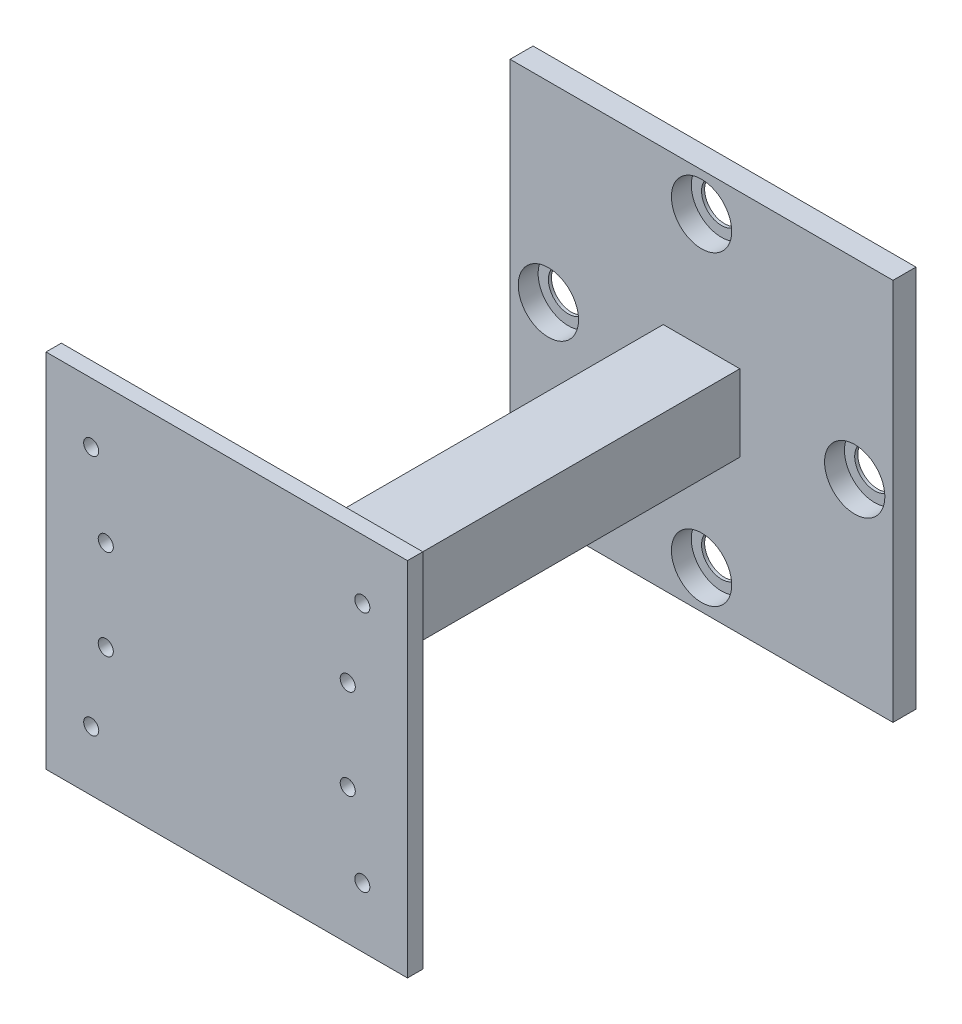
SolidWorks part; units mm, degrees
ref_plane "Front Plane" through (0, 0, 0) normal (0, 0, 1) x (1, 0, 0)
ref_plane "Top Plane" through (0, 0, 0) normal (0, 1, 0) x (1, 0, 0)
ref_plane "Right Plane" through (0, 0, 0) normal (1, 0, 0) x (0, 0, -1)
sketch "Sketch2" plane through (0, 0, 0) normal (0, 0, 1) x (1, 0, 0)
  line L0 (0, 0) -> (63.5, 0)
  line L1 (63.5, 0) -> (63.5, 63.5)
  line L2 (63.5, 63.5) -> (0, 63.5)
  line L3 (0, 63.5) -> (0, 0)
  dimension "D1" = 63.5
  dimension "D2" = 63.5
extrude "Boss-Extrude2" add sketch "Sketch2" along normal blind 3.81
sketch "Sketch3" plane through (0, 0, 3.81) normal (0, 0, 1) x (1, 0, 0)
  line L0 (25.4, 38.1) -> (25.4, 25.4)
  line L1 (25.4, 25.4) -> (38.1, 25.4)
  line L2 (38.1, 25.4) -> (38.1, 38.1)
  line L3 (38.1, 38.1) -> (25.4, 38.1)
  line L4 (0, 0) -> (63.5, 0) construction
  line L5 (63.5, 0) -> (63.5, 63.5) construction
  dimension "D1" = 12.7
  dimension "D2" = 12.7
  dimension "D3" = 25.4
  dimension "D4" = 25.4
extrude "Boss-Extrude3" add sketch "Sketch3" along normal blind 76.2
sketch "Sketch14" plane through (0, 0, 80.01) normal (0, 0, 1) x (1, 0, 0)
  line L0 (1.778, 61.722) -> (61.722, 61.722)
  line L1 (61.722, 61.722) -> (61.722, 1.778)
  line L2 (61.722, 1.778) -> (1.778, 1.778)
  line L3 (1.778, 1.778) -> (1.778, 61.722)
  line L4 (63.5, 63.5) -> (0, 63.5) construction
  line L5 (0, 63.5) -> (0, 0) construction
  dimension "D1" = 59.944
  dimension "D2" = 59.944
  dimension "D3" = 1.778
  dimension "D4" = 1.778
extrude "Boss-Extrude6" add sketch "Sketch14" along normal blind 2.54
hole_wizard "CBORE for M6 SBHCS2" positions "Sketch17" profile "Sketch16" counterbore size "M6" standard "ANSI Metric"
sketch "Sketch17" plane through (0, 0, 3.81) normal (0, 0, 1) x (1, 0, 0)
  line L0 (63.5, 63.5) -> (0, 63.5) construction
  line L1 (0, 63.5) -> (0, 0) construction
  line L2 (0, 0) -> (63.5, 0) construction
  line L3 (63.5, 0) -> (63.5, 63.5) construction
  point P0 (57.15, 31.75)
  point P2 (31.75, 6.35)
  point P4 (31.75, 57.15)
  point P6 (6.35, 31.75)
  dimension "D1" = 6.35
  dimension "D2" = 31.75
  dimension "D3" = 6.35
  dimension "D4" = 31.75
  dimension "D5" = 6.35
  dimension "D6" = 31.75
  dimension "D7" = 6.35
  dimension "D8" = 31.75
sketch "Sketch16" plane through (57.15, 31.75, 3.81) normal (1, 0, 0) x (0, -1, 0)
  line L0 (0, 0) -> (0, 9.6028)
  line L1 (0, 9.6028) -> (3.3, 7.62)
  line L2 (3.3, 7.62) -> (3.3, 3.3)
  line L3 (3.3, 3.3) -> (5, 3.3)
  line L4 (5, 3.3) -> (5, 0)
  line L5 (5, 0) -> (0, 0)
  line L10 (0, 9.6028) -> (-3.3, 7.62) construction
  line L11 (0, -6.35) -> (0, 107.95) construction
  dimension "Hole Dia." = 6.6
  dimension "Hole Depth" = 7.62
  dimension "C'Bore Dia." = 10
  dimension "C'Bore Depth" = 3.3
  dimension "Drill Angle" = 118
hole_wizard "Tap Drill for M3x0.5 Tap2" positions "Sketch18" profile "Sketch19" hole size "M3x0.5" standard "ANSI Metric"
sketch "Sketch18" plane through (0, 0, 82.55) normal (0, 0, 1) x (1, 0, 0)
  line L0 (61.722, 1.778) -> (61.722, 61.722) construction
  line L1 (1.778, 1.778) -> (61.722, 1.778) construction
  line L2 (1.778, 61.722) -> (1.778, 1.778) construction
  line L3 (61.722, 61.722) -> (1.778, 61.722) construction
  point P0 (9.271, 51.816)
  point P2 (9.271, 11.684)
  point P4 (54.229, 11.684)
  point P6 (54.229, 51.816)
  point P8 (11.684, 39.243)
  point P10 (11.684, 24.257)
  point P12 (51.816, 39.243)
  point P14 (51.816, 24.257)
  dimension "D1" = 7.493
  dimension "D2" = 9.906
  dimension "D3" = 7.493
  dimension "D4" = 9.906
  dimension "D5" = 7.493
  dimension "D6" = 9.906
  dimension "D7" = 7.493
  dimension "D8" = 9.906
  dimension "D9" = 9.906
  dimension "D10" = 22.479
  dimension "D11" = 9.906
  dimension "D12" = 22.479
  dimension "D13" = 9.906
  dimension "D14" = 22.479
  dimension "D15" = 9.906
  dimension "D16" = 22.479
sketch "Sketch19" plane through (9.271, 51.816, 82.55) normal (1, 0, 0) x (0, -1, 0)
  line L0 (0, 0) -> (0, 8.3711)
  line L1 (0, 8.3711) -> (1.25, 7.62)
  line L2 (1.25, 7.62) -> (1.25, 0)
  line L5 (1.25, 0) -> (0, 0)
  line L10 (0, 8.3711) -> (-1.25, 7.62) construction
  line L11 (0, -6.35) -> (0, 107.95) construction
  dimension "Hole Dia." = 2.5
  dimension "Hole Depth" = 7.62
  dimension "Drill Angle" = 118
